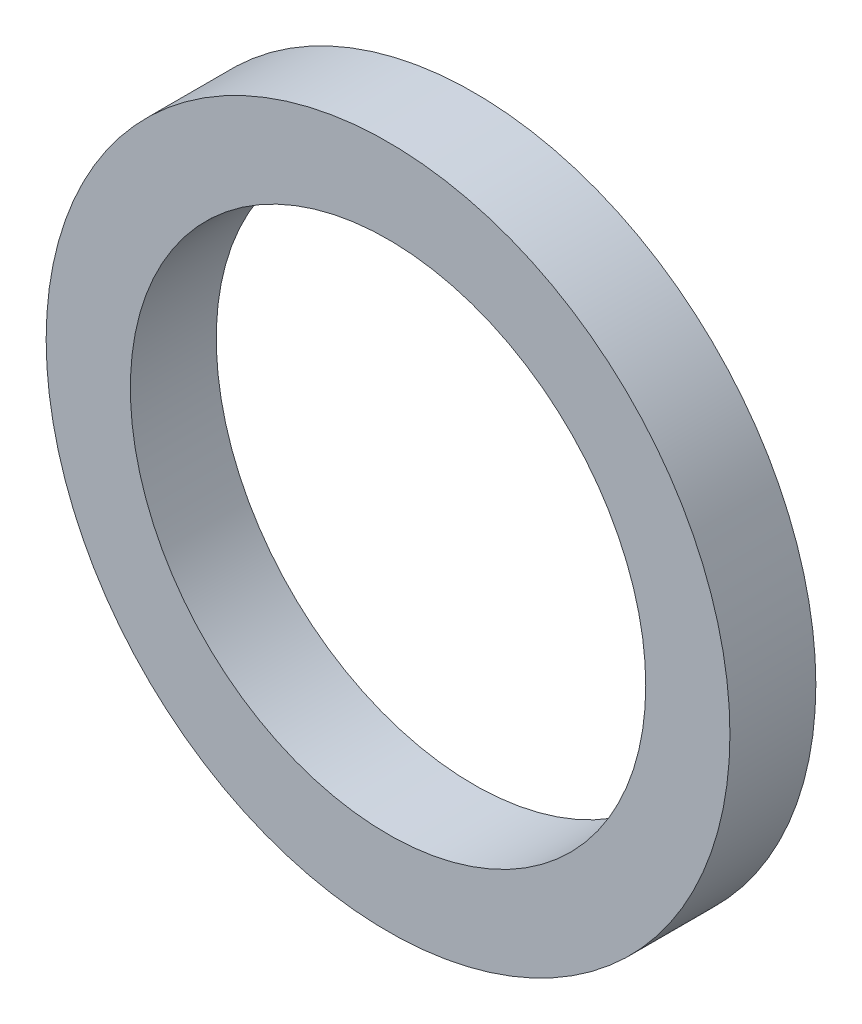
SolidWorks part; units mm, degrees
ref_plane "Front Plane" through (0, 0, 0) normal (0, 0, 1) x (1, 0, 0)
ref_plane "Top Plane" through (0, 0, 0) normal (0, 1, 0) x (1, 0, 0)
ref_plane "Right Plane" through (0, 0, 0) normal (1, 0, 0) x (0, 0, -1)
sketch "Sketch1" plane through (0, 0, 0) normal (0, 0, 1) x (1, 0, 0)
  circle A0 centre (0, 0) radius 25.273
  dimension "D1" = 50.546
extrude "Boss-Extrude1" add sketch "Sketch1" along normal blind 6.35
sketch "Sketch2" plane through (0, 0, 6.35) normal (0, 0, 1) x (1, 0, 0)
  circle A0 centre (0, 0) radius 19.05
  dimension "D1" = 38.1
extrude "Cut-Extrude1" cut sketch "Sketch2" against normal through all
sketch "Sketch4" plane through (0, 0, 6.35) normal (0, 0, 1) x (1, 0, 0)
  point P0 (0, 22.225)
  point P1 (19.2474, -11.1125)
  point P5 (-19.2474, -11.1125)
  point P6 (0, 0)
  dimension "D1" = 22.225
  dimension "D2" = 3
